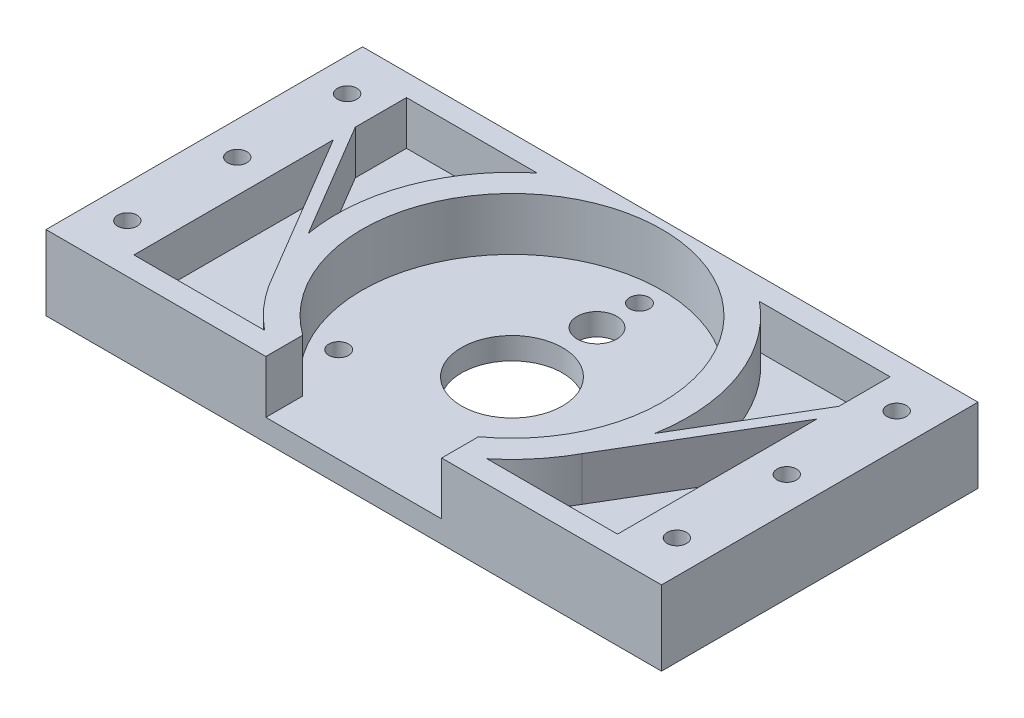
SolidWorks part; units mm, degrees
ref_plane "Front Plane" through (0, 0, 0) normal (0, 0, 1) x (1, 0, 0)
ref_plane "Top Plane" through (0, 0, 0) normal (0, 1, 0) x (1, 0, 0)
ref_plane "Right Plane" through (0, 0, 0) normal (1, 0, 0) x (0, 0, -1)
sketch "Sketch1" plane through (0, 0, 0) normal (0, 1, 0) x (1, 0, 0)
  line L1 (-70, 36) -> (70, 36)
  line L2 (-70, 36) -> (-70, -36)
  line L3 (-70, -36) -> (70, -36)
  line L4 (70, 36) -> (70, -36)
  line L5 (-70, 36) -> (70, -36) construction
  line L6 (-70, -36) -> (70, 36) construction
  point P0 (0, 0)
  dimension "D1" = 72
  dimension "D2" = 140
extrude "Boss-Extrude1" add sketch "Sketch1" along normal blind 17
sketch "Sketch2" plane through (0, 17, 0) normal (0, 1, 0) x (1, 0, 0)
  circle A0 centre (0, 0) radius 34.1
  dimension "D1" = 68.2
extrude "Cut-Extrude1" cut sketch "Sketch2" against normal blind 12
sketch "Sketch3" plane through (0, 0, 36) normal (0, 0, 1) x (1, 0, 0)
  line L0 (-70, 17) -> (70, 17) construction
  line L1 (-20, 29) -> (20, 29)
  line L2 (-20, 29) -> (-20, 5)
  line L3 (-20, 5) -> (20, 5)
  line L4 (20, 29) -> (20, 5)
  line L5 (-20, 29) -> (20, 5) construction
  line L6 (-20, 5) -> (20, 29) construction
  point P0 (0, 17)
  point P7 (20, 17)
  dimension "D1" = 12
  dimension "D2" = 40
extrude "Cut-Extrude2" cut sketch "Sketch3" against normal blind 10
sketch "Sketch4" plane through (0, 17, 0) normal (0, 1, 0) x (1, 0, 0)
  line L0 (-15.95, 0) -> (15.95, 0) construction
  line L1 (-70, 36) -> (-70, -36) construction
  line L2 (0, -15.95) -> (0, 15.95) construction
  circle A0 centre (-62.5, 25) radius 2.2
  circle A1 centre (-62.5, 0) radius 2.2
  circle A2 centre (-62.5, -25) radius 2.2
  circle A3 centre (62.5, -25) radius 2.2
  circle A4 centre (62.5, 0) radius 2.2
  circle A5 centre (62.5, 25) radius 2.2
  point P8 (0, 0)
  point P10 (-66.8793, 3.2361)
  dimension "D4" = 4.4
  dimension "D5" = 4.4
  dimension "D6" = 4.4
  dimension "D1" = 25
  dimension "D2" = 25
  dimension "D3" = 7.5
extrude "Cut-Extrude3" cut sketch "Sketch4" against normal through all
sketch "Sketch5" plane through (0, 5, 0) normal (0, 1, 0) x (1, 0, 0)
  line L0 (0, -9.35) -> (0, 9.35) construction
  circle A0 centre (0, 29) radius 2.25
  circle A1 centre (25.0423, -14.3746) radius 2.25
  circle A2 centre (-25.0423, -14.3746) radius 2.25
  circle A3 centre (0, 19.3336) radius 4.5
  point P12 (0, 0.0836)
  dimension "D1" = 4.5
  dimension "D5" = 9
  dimension "D2" = 29
  dimension "D4" = 19.25
  dimension "D3" = 3
extrude "Cut-Extrude4" cut sketch "Sketch5" against normal through all
sketch "Sketch6" plane through (0, 17, 0) normal (0, 1, 0) x (1, 0, 0)
  line L7 (-55, 0) -> (-55, 14.355) construction
  line L8 (-9.35, 0) -> (9.35, 0) construction
  line L9 (-55, 46.2181) -> (-55, 19.355) construction
  line L10 (-55, -31) -> (-25.2784, -31) construction
  line L11 (-55, 31) -> (-25.2784, 31)
  line L12 (-55, 31) -> (-55, 19.355)
  line L13 (-55, -31) -> (-25.2784, -31)
  line L14 (70, 36) -> (-70, 36) construction
  line L15 (-70, 36) -> (-70, -36) construction
  line L16 (-70, -36) -> (-20, -36) construction
  line L17 (0, -9.35) -> (0, 9.35) construction
  line L18 (55, -31) -> (25.2784, -31)
  line L19 (55, 31) -> (55, 19.355)
  line L20 (55, 31) -> (25.2784, 31)
  line L21 (-55, 14.355) -> (-35.0938, -19.1945)
  line L22 (-55, 19.355) -> (-39.3913, -6.9515)
  line L23 (-55, 19.355) -> (-55, 46.2181) construction
  line L24 (-55, 14.355) -> (-55, -31)
  line L25 (-55, 14.355) -> (-55, -31) construction
  line L26 (55, 14.355) -> (35.0938, -19.1945)
  line L27 (55, 19.355) -> (39.3913, -6.9515)
  line L28 (55, 14.355) -> (55, -31)
  arc A1 (-25.2784, 31) -> (-39.3913, -6.9515) centre (0, 0) ccw
  arc A2 (25.2784, -31) -> (35.0938, -19.1945) centre (0, 0) ccw
  arc A3 (-35.0938, -19.1945) -> (-25.2784, -31) centre (0, 0) ccw
  arc A4 (39.3913, -6.9515) -> (25.2784, 31) centre (0, 0) ccw
  dimension "D1" = 80
  dimension "D2" = 5
  dimension "D3" = 15
  dimension "D4" = 5
  dimension "D5" = 5
  dimension "D6" = 0
extrude "Cut-Extrude5" cut sketch "Sketch6" against normal blind 10
sketch "Sketch7" plane through (0, 5, 0) normal (0, 1, 0) x (1, 0, 0)
  circle A0 centre (0, 0) radius 11.5
  dimension "D1" = 23
extrude "Cut-Extrude6" cut sketch "Sketch7" against normal blind 10
equation "\"D5@Sketch4\"=\"D4@Sketch4\""
equation "\"D6@Sketch4\"=\"D5@Sketch4\""
